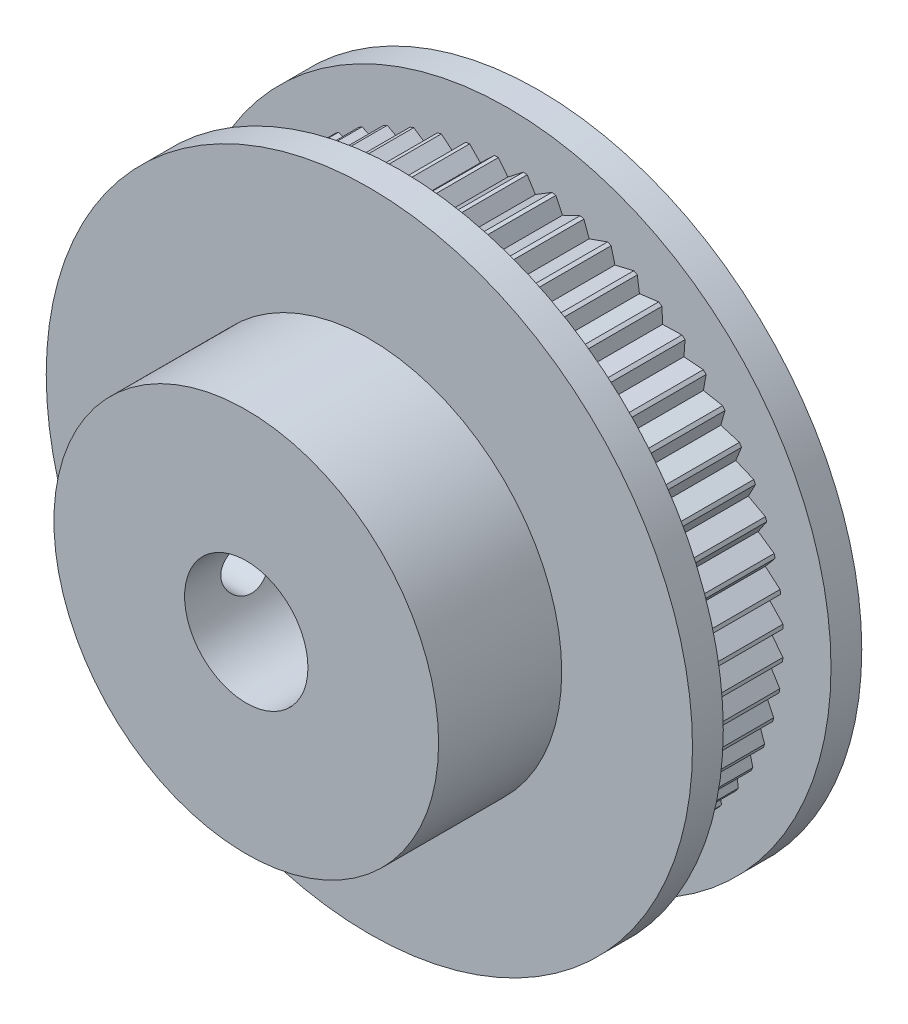
SolidWorks part; units mm, degrees
ref_plane "Front Plane" through (0, 0, 0) normal (0, 0, 1) x (1, 0, 0)
ref_plane "Top Plane" through (0, 0, 0) normal (0, 1, 0) x (1, 0, 0)
ref_plane "Right Plane" through (0, 0, 0) normal (1, 0, 0) x (0, 0, -1)
sketch "Sketch1" plane through (0, 0, 0) normal (0, 0, 1) x (1, 0, 0)
  circle A0 centre (0, 0) radius 21
extrude "Boss-Extrude1" add sketch "Sketch1" along normal blind 11
sketch "Sketch2" plane through (0, 0, 11) normal (0, 0, 1) x (1, 0, 0)
  circle A0 centre (0, 0) radius 12.5
extrude "Boss-Extrude2" add sketch "Sketch2" along normal blind 8
sketch "Sketch3" plane through (0, 0, 19) normal (0, 0, 1) x (1, 0, 0)
  circle A0 centre (0, 0) radius 4.0075
  dimension "D1" = 8.015
extrude "Cut-Extrude1" cut sketch "Sketch3" against normal blind 20
sketch "Sketch4" plane through (0, 0, 11) normal (0, 0, 1) x (1, 0, 0)
  line L0 (0, 0) -> (0, 18) construction
  line L1 (0, 18) -> (1.1673, 18) construction
  line L7 (0, 17.1038) -> (1.1673, 18)
  line L8 (1.1673, 18) -> (-0.7037, 18)
  line L9 (-0.7037, 18) -> (0, 17.1038)
  line L10 (1.7878, 17.0101) -> (3.0424, 17.7794)
  line L11 (3.0424, 17.7794) -> (1.1816, 17.975)
  line L12 (1.1816, 17.975) -> (1.7878, 17.0101)
  line L13 (3.5561, 16.7301) -> (4.8842, 17.364)
  line L14 (4.8842, 17.364) -> (3.0541, 17.753)
  line L15 (3.0541, 17.753) -> (3.5561, 16.7301)
  line L16 (5.2854, 16.2667) -> (6.6725, 16.7583)
  line L17 (6.6725, 16.7583) -> (4.893, 17.3365)
  line L18 (4.893, 17.3365) -> (5.2854, 16.2667)
  line L19 (6.9568, 15.6251) -> (8.3876, 15.969)
  line L20 (8.3876, 15.969) -> (6.6784, 16.7301)
  line L21 (6.6784, 16.7301) -> (6.9568, 15.6251)
  line L22 (8.5519, 14.8124) -> (10.0109, 15.0048)
  line L23 (10.0109, 15.0048) -> (8.3906, 15.9403)
  line L24 (8.3906, 15.9403) -> (8.5519, 14.8124)
  line L25 (10.0534, 13.8373) -> (11.5245, 13.8762)
  line L26 (11.5245, 13.8762) -> (10.0108, 14.9759)
  line L27 (10.0108, 14.9759) -> (10.0534, 13.8373)
  line L28 (11.4447, 12.7106) -> (12.9118, 12.5955)
  line L29 (12.9118, 12.5955) -> (11.5214, 13.8475)
  line L30 (11.5214, 13.8475) -> (11.4447, 12.7106)
  line L31 (12.7106, 11.4447) -> (14.1577, 11.1769)
  line L32 (14.1577, 11.1769) -> (12.9057, 12.5673)
  line L33 (12.9057, 12.5673) -> (12.7106, 11.4447)
  line L34 (13.8373, 10.0534) -> (15.2484, 9.6358)
  line L35 (15.2484, 9.6358) -> (14.1487, 11.1495)
  line L36 (14.1487, 11.1495) -> (13.8373, 10.0534)
  line L37 (14.8124, 8.5519) -> (16.1721, 7.9891)
  line L38 (16.1721, 7.9891) -> (15.2366, 9.6094)
  line L39 (15.2366, 9.6094) -> (14.8124, 8.5519)
  line L40 (15.6251, 6.9568) -> (16.9186, 6.2549)
  line L41 (16.9186, 6.2549) -> (16.1576, 7.9641)
  line L42 (16.1576, 7.9641) -> (15.6251, 6.9568)
  line L43 (16.2667, 5.2854) -> (17.4797, 4.4521)
  line L44 (17.4797, 4.4521) -> (16.9016, 6.2316)
  line L45 (16.9016, 6.2316) -> (16.2667, 5.2854)
  line L46 (16.7301, 3.5561) -> (17.8494, 2.6006)
  line L47 (17.8494, 2.6006) -> (17.4603, 4.4308)
  line L48 (17.4603, 4.4308) -> (16.7301, 3.5561)
  line L49 (17.0101, 1.7878) -> (18.0234, 0.7206)
  line L50 (18.0234, 0.7206) -> (17.8278, 2.5814)
  line L51 (17.8278, 2.5814) -> (17.0101, 1.7878)
  line L52 (17.1038, 0) -> (18, -1.1673)
  line L53 (18, -1.1673) -> (18, 0.7037)
  line L54 (18, 0.7037) -> (17.1038, 0)
  line L55 (17.0101, -1.7878) -> (17.7794, -3.0424)
  line L56 (17.7794, -3.0424) -> (17.975, -1.1816)
  line L57 (17.975, -1.1816) -> (17.0101, -1.7878)
  line L58 (16.7301, -3.5561) -> (17.364, -4.8842)
  line L59 (17.364, -4.8842) -> (17.753, -3.0541)
  line L60 (17.753, -3.0541) -> (16.7301, -3.5561)
  line L61 (16.2667, -5.2854) -> (16.7583, -6.6725)
  line L62 (16.7583, -6.6725) -> (17.3365, -4.893)
  line L63 (17.3365, -4.893) -> (16.2667, -5.2854)
  line L64 (15.6251, -6.9568) -> (15.969, -8.3876)
  line L65 (15.969, -8.3876) -> (16.7301, -6.6784)
  line L66 (16.7301, -6.6784) -> (15.6251, -6.9568)
  line L67 (14.8124, -8.5519) -> (15.0048, -10.0109)
  line L68 (15.0048, -10.0109) -> (15.9403, -8.3906)
  line L69 (15.9403, -8.3906) -> (14.8124, -8.5519)
  line L70 (13.8373, -10.0534) -> (13.8762, -11.5245)
  line L71 (13.8762, -11.5245) -> (14.9759, -10.0108)
  line L72 (14.9759, -10.0108) -> (13.8373, -10.0534)
  line L73 (12.7106, -11.4447) -> (12.5955, -12.9118)
  line L74 (12.5955, -12.9118) -> (13.8475, -11.5214)
  line L75 (13.8475, -11.5214) -> (12.7106, -11.4447)
  line L76 (11.4447, -12.7106) -> (11.1769, -14.1577)
  line L77 (11.1769, -14.1577) -> (12.5673, -12.9057)
  line L78 (12.5673, -12.9057) -> (11.4447, -12.7106)
  line L79 (10.0534, -13.8373) -> (9.6358, -15.2484)
  line L80 (9.6358, -15.2484) -> (11.1495, -14.1487)
  line L81 (11.1495, -14.1487) -> (10.0534, -13.8373)
  line L82 (8.5519, -14.8124) -> (7.9891, -16.1721)
  line L83 (7.9891, -16.1721) -> (9.6094, -15.2366)
  line L84 (9.6094, -15.2366) -> (8.5519, -14.8124)
  line L85 (6.9568, -15.6251) -> (6.2549, -16.9186)
  line L86 (6.2549, -16.9186) -> (7.9641, -16.1576)
  line L87 (7.9641, -16.1576) -> (6.9568, -15.6251)
  line L88 (5.2854, -16.2667) -> (4.4521, -17.4797)
  line L89 (4.4521, -17.4797) -> (6.2316, -16.9016)
  line L90 (6.2316, -16.9016) -> (5.2854, -16.2667)
  line L91 (3.5561, -16.7301) -> (2.6006, -17.8494)
  line L92 (2.6006, -17.8494) -> (4.4308, -17.4603)
  line L93 (4.4308, -17.4603) -> (3.5561, -16.7301)
  line L94 (1.7878, -17.0101) -> (0.7206, -18.0234)
  line L95 (0.7206, -18.0234) -> (2.5814, -17.8278)
  line L96 (2.5814, -17.8278) -> (1.7878, -17.0101)
  line L97 (0, -17.1038) -> (-1.1673, -18)
  line L98 (-1.1673, -18) -> (0.7037, -18)
  line L99 (0.7037, -18) -> (0, -17.1038)
  line L100 (-1.7878, -17.0101) -> (-3.0424, -17.7794)
  line L101 (-3.0424, -17.7794) -> (-1.1816, -17.975)
  line L102 (-1.1816, -17.975) -> (-1.7878, -17.0101)
  line L103 (-3.5561, -16.7301) -> (-4.8842, -17.364)
  line L104 (-4.8842, -17.364) -> (-3.0541, -17.753)
  line L105 (-3.0541, -17.753) -> (-3.5561, -16.7301)
  line L106 (-5.2854, -16.2667) -> (-6.6725, -16.7583)
  line L107 (-6.6725, -16.7583) -> (-4.893, -17.3365)
  line L108 (-4.893, -17.3365) -> (-5.2854, -16.2667)
  line L109 (-6.9568, -15.6251) -> (-8.3876, -15.969)
  line L110 (-8.3876, -15.969) -> (-6.6784, -16.7301)
  line L111 (-6.6784, -16.7301) -> (-6.9568, -15.6251)
  line L112 (-8.5519, -14.8124) -> (-10.0109, -15.0048)
  line L113 (-10.0109, -15.0048) -> (-8.3906, -15.9403)
  line L114 (-8.3906, -15.9403) -> (-8.5519, -14.8124)
  line L115 (-10.0534, -13.8373) -> (-11.5245, -13.8762)
  line L116 (-11.5245, -13.8762) -> (-10.0108, -14.9759)
  line L117 (-10.0108, -14.9759) -> (-10.0534, -13.8373)
  line L118 (-11.4447, -12.7106) -> (-12.9118, -12.5955)
  line L119 (-12.9118, -12.5955) -> (-11.5214, -13.8475)
  line L120 (-11.5214, -13.8475) -> (-11.4447, -12.7106)
  line L121 (-12.7106, -11.4447) -> (-14.1577, -11.1769)
  line L122 (-14.1577, -11.1769) -> (-12.9057, -12.5673)
  line L123 (-12.9057, -12.5673) -> (-12.7106, -11.4447)
  line L124 (-13.8373, -10.0534) -> (-15.2484, -9.6358)
  line L125 (-15.2484, -9.6358) -> (-14.1487, -11.1495)
  line L126 (-14.1487, -11.1495) -> (-13.8373, -10.0534)
  line L127 (-14.8124, -8.5519) -> (-16.1721, -7.9891)
  line L128 (-16.1721, -7.9891) -> (-15.2366, -9.6094)
  line L129 (-15.2366, -9.6094) -> (-14.8124, -8.5519)
  line L130 (-15.6251, -6.9568) -> (-16.9186, -6.2549)
  line L131 (-16.9186, -6.2549) -> (-16.1576, -7.9641)
  line L132 (-16.1576, -7.9641) -> (-15.6251, -6.9568)
  line L133 (-16.2667, -5.2854) -> (-17.4797, -4.4521)
  line L134 (-17.4797, -4.4521) -> (-16.9016, -6.2316)
  line L135 (-16.9016, -6.2316) -> (-16.2667, -5.2854)
  line L136 (-16.7301, -3.5561) -> (-17.8494, -2.6006)
  line L137 (-17.8494, -2.6006) -> (-17.4603, -4.4308)
  line L138 (-17.4603, -4.4308) -> (-16.7301, -3.5561)
  line L139 (-17.0101, -1.7878) -> (-18.0234, -0.7206)
  line L140 (-18.0234, -0.7206) -> (-17.8278, -2.5814)
  line L141 (-17.8278, -2.5814) -> (-17.0101, -1.7878)
  line L142 (-17.1038, 0) -> (-18, 1.1673)
  line L143 (-18, 1.1673) -> (-18, -0.7037)
  line L144 (-18, -0.7037) -> (-17.1038, 0)
  line L145 (-17.0101, 1.7878) -> (-17.7794, 3.0424)
  line L146 (-17.7794, 3.0424) -> (-17.975, 1.1816)
  line L147 (-17.975, 1.1816) -> (-17.0101, 1.7878)
  line L148 (-16.7301, 3.5561) -> (-17.364, 4.8842)
  line L149 (-17.364, 4.8842) -> (-17.753, 3.0541)
  line L150 (-17.753, 3.0541) -> (-16.7301, 3.5561)
  line L151 (-16.2667, 5.2854) -> (-16.7583, 6.6725)
  line L152 (-16.7583, 6.6725) -> (-17.3365, 4.893)
  line L153 (-17.3365, 4.893) -> (-16.2667, 5.2854)
  line L154 (-15.6251, 6.9568) -> (-15.969, 8.3876)
  line L155 (-15.969, 8.3876) -> (-16.7301, 6.6784)
  line L156 (-16.7301, 6.6784) -> (-15.6251, 6.9568)
  line L157 (-14.8124, 8.5519) -> (-15.0048, 10.0109)
  line L158 (-15.0048, 10.0109) -> (-15.9403, 8.3906)
  line L159 (-15.9403, 8.3906) -> (-14.8124, 8.5519)
  line L160 (-13.8373, 10.0534) -> (-13.8762, 11.5245)
  line L161 (-13.8762, 11.5245) -> (-14.9759, 10.0108)
  line L162 (-14.9759, 10.0108) -> (-13.8373, 10.0534)
  line L163 (-12.7106, 11.4447) -> (-12.5955, 12.9118)
  line L164 (-12.5955, 12.9118) -> (-13.8475, 11.5214)
  line L165 (-13.8475, 11.5214) -> (-12.7106, 11.4447)
  line L166 (-11.4447, 12.7106) -> (-11.1769, 14.1577)
  line L167 (-11.1769, 14.1577) -> (-12.5673, 12.9057)
  line L168 (-12.5673, 12.9057) -> (-11.4447, 12.7106)
  line L169 (-10.0534, 13.8373) -> (-9.6358, 15.2484)
  line L170 (-9.6358, 15.2484) -> (-11.1495, 14.1487)
  line L171 (-11.1495, 14.1487) -> (-10.0534, 13.8373)
  line L172 (-8.5519, 14.8124) -> (-7.9891, 16.1721)
  line L173 (-7.9891, 16.1721) -> (-9.6094, 15.2366)
  line L174 (-9.6094, 15.2366) -> (-8.5519, 14.8124)
  line L175 (-6.9568, 15.6251) -> (-6.2549, 16.9186)
  line L176 (-6.2549, 16.9186) -> (-7.9641, 16.1576)
  line L177 (-7.9641, 16.1576) -> (-6.9568, 15.6251)
  line L178 (-5.2854, 16.2667) -> (-4.4521, 17.4797)
  line L179 (-4.4521, 17.4797) -> (-6.2316, 16.9016)
  line L180 (-6.2316, 16.9016) -> (-5.2854, 16.2667)
  line L181 (-3.5561, 16.7301) -> (-2.6006, 17.8494)
  line L182 (-2.6006, 17.8494) -> (-4.4308, 17.4603)
  line L183 (-4.4308, 17.4603) -> (-3.5561, 16.7301)
  line L184 (-1.7878, 17.0101) -> (-0.7206, 18.0234)
  line L185 (-0.7206, 18.0234) -> (-2.5814, 17.8278)
  line L186 (-2.5814, 17.8278) -> (-1.7878, 17.0101)
  point P187 (0, 0)
  dimension "D1" = 60
extrude "Cut-Extrude5" cut sketch "Sketch4" against normal blind 7 from offset 2 offset against normal yes
sketch "Sketch5" plane through (0, 0, 11) normal (0, 0, 1) x (1, 0, 0)
  circle A0 centre (0, 0) radius 17.9
  circle A1 centre (0, 0) radius 21.0426
extrude "Cut-Extrude6" cut sketch "Sketch5" against normal blind 7 from offset 2 offset against normal yes
ref_plane "Plane1" through (-12.5, 0, 0) normal (-1, 0, 0) x (0, 0, 1)
sketch "Sketch6" plane through (-12.5, 0, 0) normal (-1, 0, 0) x (0, 0, 1)
  line L0 (19, -12.5) -> (19, 12.5) construction
  line L1 (19, 12.5) -> (11, 12.5) construction
  circle A0 centre (15, 0) radius 2
  dimension "D1" = 4
  dimension "D2" = 4
  dimension "D3" = 12.5
hole_wizard "M4x0.7 Tapped Hole1" positions "Sketch7" profile "Sketch8" tap size "M4x0.7" standard "ANSI Metric"
sketch "Sketch7" plane through (-12.5, 0, 0) normal (-1, 0, 0) x (0, 0, 1)
  point P0 (15, 0)
sketch "Sketch8" plane through (-12.5, 0, 15) normal (0, 1, 0) x (0, 0, 1)
  line L0 (0, 0) -> (0, 12.4914)
  line L1 (0, 12.4914) -> (1.65, 11.5)
  line L2 (1.65, 11.5) -> (1.65, 0)
  line L5 (1.65, 0) -> (0, 0)
  line L10 (0, 12.4914) -> (-1.65, 11.5) construction
  line L11 (0, -6.35) -> (0, 107.95) construction
  dimension "Tap Drill Dia." = 3.3
  dimension "Tap Drill Depth" = 11.5
  dimension "Drill Angle" = 118
